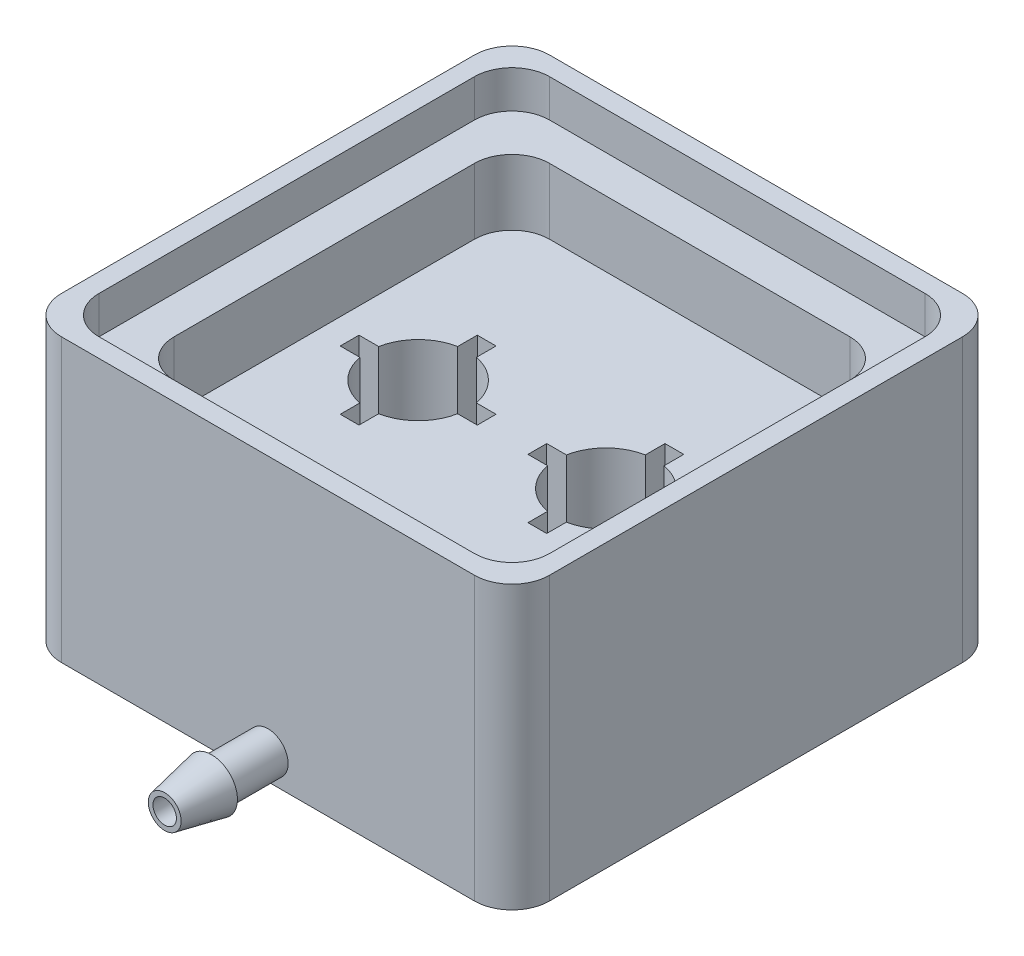
SolidWorks part; units mm, degrees
ref_plane "Front Plane" through (0, 0, 0) normal (0, 0, 1) x (1, 0, 0)
ref_plane "Top Plane" through (0, 0, 0) normal (0, 1, 0) x (1, 0, 0)
ref_plane "Right Plane" through (0, 0, 0) normal (1, 0, 0) x (0, 0, -1)
sketch "Sketch1" plane through (0, 0, 0) normal (0, 1, 0) x (1, 0, 0)
  line L0 (-5, 0) -> (5, 0) construction
  line L1 (-11, -13) -> (11, -13)
  line L2 (-13, -11) -> (-13, 11)
  line L3 (-11, 13) -> (11, 13)
  line L4 (13, -11) -> (13, 11)
  line L5 (-13, -13) -> (13, 13) construction
  line L6 (-13, 13) -> (13, -13) construction
  arc A0 (-13, 11) -> (-11, 13) centre (-11, 11) cw
  arc A1 (11, 13) -> (13, 11) centre (11, 11) cw
  arc A2 (-13, -11) -> (-11, -13) centre (-11, -11) ccw
  arc A3 (13, -11) -> (11, -13) centre (11, -11) cw
  circle A4 centre (5, 0) radius 2.65
  circle A5 centre (-5, 0) radius 2.65
  point P0 (0, 0)
  point P21 (0, 0)
  dimension "D3" = 2
  dimension "D4" = 2
  dimension "D6" = 5.3
  dimension "D7" = 5.3
  dimension "D1" = 26
  dimension "D2" = 26
  dimension "D5" = 10
extrude "Boss-Extrude1" add sketch "Sketch1" along normal blind 9.53
sketch "Sketch2" plane through (0, 9.53, 0) normal (0, 1, 0) x (1, 0, 0)
  line L0 (-5, 0) -> (5, 0) construction
  line L2 (-8.65, -0.5) -> (-1.35, -0.5)
  line L3 (-8.65, -0.5) -> (-8.65, 0.5)
  line L4 (-8.65, 0.5) -> (-1.35, 0.5)
  line L5 (-1.35, -0.5) -> (-1.35, 0.5)
  line L6 (-8.65, -0.5) -> (-1.35, 0.5) construction
  line L7 (-8.65, 0.5) -> (-1.35, -0.5) construction
  line L8 (-5.5, -3.65) -> (-4.5, -3.65)
  line L9 (-5.5, -3.65) -> (-5.5, 3.65)
  line L10 (-5.5, 3.65) -> (-4.5, 3.65)
  line L11 (-4.5, -3.65) -> (-4.5, 3.65)
  line L12 (-5.5, -3.65) -> (-4.5, 3.65) construction
  line L13 (-5.5, 3.65) -> (-4.5, -3.65) construction
  line L14 (4.5, -3.65) -> (5.5, -3.65)
  line L15 (4.5, -3.65) -> (4.5, 3.65)
  line L16 (4.5, 3.65) -> (5.5, 3.65)
  line L17 (5.5, -3.65) -> (5.5, 3.65)
  line L18 (4.5, -3.65) -> (5.5, 3.65) construction
  line L19 (4.5, 3.65) -> (5.5, -3.65) construction
  line L20 (1.35, -0.5) -> (8.65, -0.5)
  line L21 (1.35, -0.5) -> (1.35, 0.5)
  line L22 (1.35, 0.5) -> (8.65, 0.5)
  line L23 (8.65, -0.5) -> (8.65, 0.5)
  line L24 (1.35, -0.5) -> (8.65, 0.5) construction
  line L25 (1.35, 0.5) -> (8.65, -0.5) construction
  point P3 (0, 0)
  circle M15 centre (5, 0) radius 2.65
  circle M16 centre (-5, 0) radius 2.65
  dimension "D1" = 10
  dimension "D2" = 7.3
  dimension "D3" = 7.3
  dimension "D4" = 7.3
  dimension "D5" = 7.3
  dimension "D6" = 1
  dimension "D7" = 1
  dimension "D8" = 1
  dimension "D9" = 1
extrude "Cut-Extrude1" cut sketch "Sketch2" against normal blind 8.785 contours L17 L16 L15 M15 | L20 L23 L22 M15 | L14 L17 L15 M15 | L22 L21 L20 M15 | L2 L5 L4 M16 | L11 L10 L9 M16 | L4 L3 L2 M16 | L8 L11 L9 M16
sketch "Sketch3" plane through (0, 0, 0) normal (1, 0, 0) x (0, 0, -1)
  line L0 (-13, 0.3) -> (-16, 0.3)
  line L1 (-13, 9.53) -> (-13, 0) construction
  line L2 (-16, 0.3) -> (-16, 0)
  line L3 (-16, 0) -> (-18.5, 0.5)
  line L4 (-18.5, 0.5) -> (-18.5, 0.75)
  line L5 (-18.5, 0.75) -> (-13, 0.75)
  line L6 (-13, 0.75) -> (-13, 0.3)
  line L7 (-13, 1.375) -> (-13.6025, 1.375) construction
  line L8 (-11, 0) -> (11, 0) construction
  dimension "D1" = 2.5
  dimension "D2" = 3
  dimension "D3" = 0.875
  dimension "D4" = 1.075
  dimension "D5" = 0.625
  dimension "D6" = 1.375
revolve "Revolve1" add sketch "Sketch3" angle 360 about L7
sketch "Sketch10" plane through (0, 0, 0) normal (1, 0, 0) x (0, 0, -1)
  circle A0 centre (0, 1.375) radius 0.625
extrude "Cut-Extrude3" cut sketch "Sketch10" against normal up to next and the other way up to next
sketch "Sketch5" plane through (0, 0, 13) normal (0, 0, 1) x (1, 0, 0)
  circle A0 centre (0, 1.375) radius 0.625
  dimension "D1" = 1.25
extrude "Cut-Extrude2" cut sketch "Sketch5" against normal up to next
sketch "Sketch6" plane through (0, 9.53, 0) normal (0, 1, 0) x (1, 0, 0)
  line L1 (-11, -13) -> (11, -13)
  line L2 (-13, -11) -> (-13, 11)
  line L3 (-11, 13) -> (11, 13)
  line L4 (13, -11) -> (13, 11)
  line L5 (-13, -13) -> (13, 13) construction
  line L6 (-13, 13) -> (13, -13) construction
  line L7 (-8, -10) -> (8, -10)
  line L8 (-10, -8) -> (-10, 8)
  line L9 (-8, 10) -> (8, 10)
  line L10 (10, -8) -> (10, 8)
  line L11 (-10, -10) -> (10, 10) construction
  line L12 (-10, 10) -> (10, -10) construction
  arc A0 (-13, -11) -> (-11, -13) centre (-11, -11) ccw
  arc A1 (13, -11) -> (11, -13) centre (11, -11) cw
  arc A2 (13, 11) -> (11, 13) centre (11, 11) ccw
  arc A3 (-11, 13) -> (-13, 11) centre (-11, 11) ccw
  arc A4 (-10, -8) -> (-8, -10) centre (-8, -8) ccw
  arc A5 (8, -10) -> (10, -8) centre (8, -8) ccw
  arc A6 (10, 8) -> (8, 10) centre (8, 8) ccw
  arc A7 (-8, 10) -> (-10, 8) centre (-8, 8) ccw
  point P0 (0, 0)
  point P18 (0, 0)
  dimension "D3" = 2
  dimension "D1" = 26
  dimension "D2" = 26
  dimension "D6" = 2
  dimension "D4" = 3
  dimension "D5" = 3
extrude "Boss-Extrude2" add sketch "Sketch6" along normal blind 3.5
sketch "Sketch8" plane through (0, 13.03, 0) normal (0, 1, 0) x (1, 0, 0)
  line L1 (-11, -13) -> (11, -13)
  line L2 (-13, -11) -> (-13, 11)
  line L3 (-11, 13) -> (11, 13)
  line L4 (13, -11) -> (13, 11)
  line L5 (-13, -13) -> (13, 13) construction
  line L6 (-13, 13) -> (13, -13) construction
  line L7 (-10, -12) -> (10, -12)
  line L8 (-12, -10) -> (-12, 10)
  line L9 (-10, 12) -> (10, 12)
  line L10 (12, -10) -> (12, 10)
  line L11 (-12, -12) -> (12, 12) construction
  line L12 (-12, 12) -> (12, -12) construction
  arc A0 (13, 11) -> (11, 13) centre (11, 11) ccw
  arc A1 (13, -11) -> (11, -13) centre (11, -11) cw
  arc A2 (-13, -11) -> (-11, -13) centre (-11, -11) ccw
  arc A3 (-13, 11) -> (-11, 13) centre (-11, 11) cw
  arc A4 (-12, -10) -> (-10, -12) centre (-10, -10) ccw
  arc A5 (10, -12) -> (12, -10) centre (10, -10) ccw
  arc A6 (12, 10) -> (10, 12) centre (10, 10) ccw
  arc A7 (-12, 10) -> (-10, 12) centre (-10, 10) cw
  point P0 (0, 0)
  point P18 (0, 0)
  dimension "D3" = 2
  dimension "D1" = 26
  dimension "D2" = 26
  dimension "D6" = 2
  dimension "D4" = 1
  dimension "D5" = 1
extrude "Boss-Extrude3" add sketch "Sketch8" along normal blind 2
equation "\"D2@Sketch1\"=\"D1@Sketch1\""
equation "\"D7@Sketch1\"=\"D6@Sketch1\""
equation "\"D3@Sketch2\"=\"D2@Sketch2\""
equation "\"D2@Sketch2\"=\"D6@Sketch1\"+2mm"
equation "\"D4@Sketch2\"=\"D2@Sketch2\""
equation "\"D5@Sketch2\"=\"D2@Sketch2\""
equation "\"D7@Sketch2\"=\"D6@Sketch2\""
equation "\"D8@Sketch2\"=\"D6@Sketch2\""
equation "\"D9@Sketch2\"=\"D6@Sketch2\""
equation "\"D1@Sketch6\"=\"D1@Sketch1\""
equation "\"D2@Sketch6\"=\"D1@Sketch1\""
equation "\"D5@Sketch6\"=\"D4@Sketch6\""
equation "\"D1@Sketch8\"=\"D1@Sketch1\""
equation "\"D2@Sketch8\"=\"D1@Sketch1\""
equation "\"D1@Sketch2\"=\"D5@Sketch1\""
